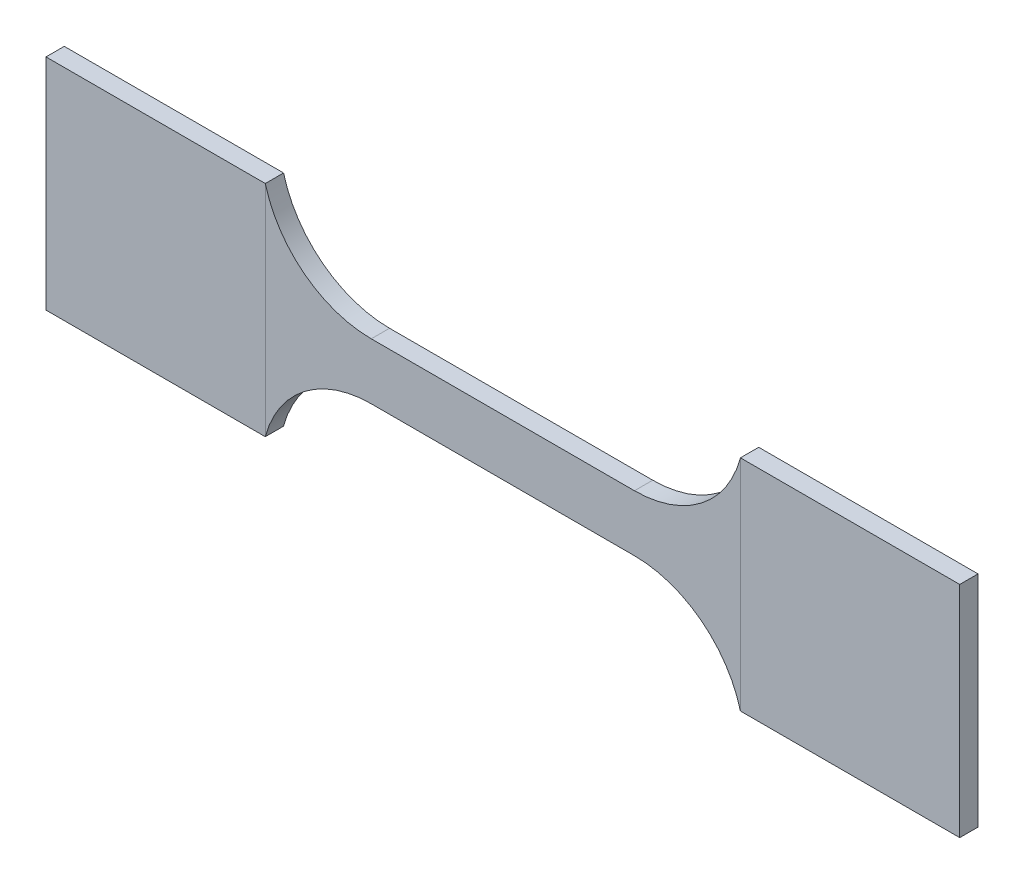
SolidWorks part; units mm, degrees
ref_plane "Front Plane" through (0, 0, 0) normal (0, 0, 1) x (1, 0, 0)
ref_plane "Top Plane" through (0, 0, 0) normal (0, 1, 0) x (1, 0, 0)
ref_plane "Right Plane" through (0, 0, 0) normal (1, 0, 0) x (0, 0, -1)
sketch "Sketch1" plane through (0, 0, 0) normal (0, 0, 1) x (1, 0, 0)
  line L0 (-87.1885, 6.8231) -> (-87.1885, 36.8231)
  line L1 (-87.1885, 36.8231) -> (-57.1885, 36.8231)
  line L2 (-42.691, 25.6731) -> (-6.691, 25.6731)
  line L4 (37.8065, 6.8231) -> (37.8065, 36.8231)
  line L5 (37.8065, 36.8231) -> (7.8065, 36.8231)
  line L7 (37.8065, 6.8231) -> (7.8065, 6.8231)
  line L8 (-42.691, 17.9731) -> (-6.691, 17.9731)
  line L9 (-87.1885, 6.8231) -> (-57.1885, 6.8231)
  arc A0 (-57.1885, 36.8231) -> (-42.691, 25.6731) centre (-42.691, 40.6731) ccw
  arc A1 (7.8065, 36.8231) -> (-6.691, 25.6731) centre (-6.691, 40.6731) cw
  arc A2 (7.8065, 6.8231) -> (-6.691, 17.9731) centre (-6.691, 2.9731) ccw
  arc A3 (-57.1885, 6.8231) -> (-42.691, 17.9731) centre (-42.691, 2.9731) cw
  point P3 (-42.691, 40.6731)
  dimension "D1" = 30
  dimension "D2" = 7.7
  dimension "D3" = 30
  dimension "D4" = 30
  dimension "D5" = 30
  dimension "D6" = 36
extrude "Boss-Extrude1" add sketch "Sketch1" along normal blind 2.5
sketch "Sketch5" plane through (0, 0, 2.5) normal (0, 0, 1) x (1, 0, 0)
  line L0 (-57.1885, 36.8231) -> (-57.1885, 6.8231)
  line L1 (7.8065, 36.8231) -> (7.8065, 6.8231)
split "Split1" trim tools "Sketch5" bodies to split 101 resulting bodies 102 103 104
